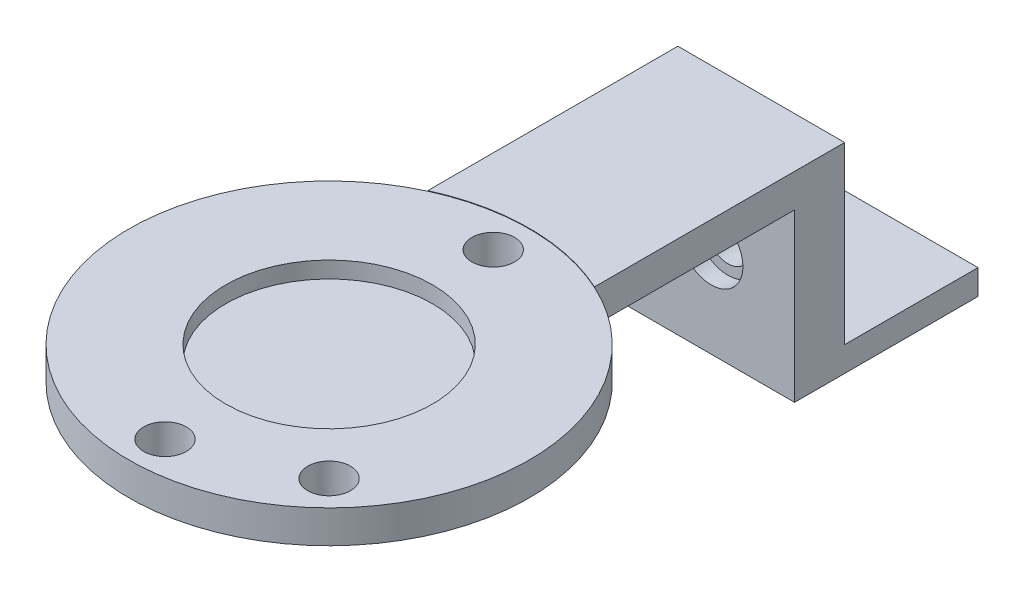
SolidWorks part; units mm, degrees
ref_plane "Front Plane" through (0, 0, 0) normal (0, 0, 1) x (1, 0, 0)
ref_plane "Top Plane" through (0, 0, 0) normal (0, 1, 0) x (1, 0, 0)
ref_plane "Right Plane" through (0, 0, 0) normal (1, 0, 0) x (0, 0, -1)
sketch "Sketch1" plane through (0, 0, 0) normal (0, 1, 0) x (1, 0, 0)
  circle A0 centre (0, 0) radius 30.5
extrude "Boss-Extrude1" add sketch "Sketch1" along normal blind 5
sketch "Sketch2" plane through (0, 5, 0) normal (0, 1, 0) x (1, 0, 0)
  circle A0 centre (0, 0) radius 15.75
extrude "Cut-Extrude1" cut sketch "Sketch2" against normal blind 2.5
sketch "Sketch3" plane through (0, 0, 0) normal (0, -1, 0) x (1, 0, 0)
  circle A0 centre (0, 0) radius 15.75
extrude "Boss-Extrude2" add sketch "Sketch3" along normal blind 2.5
sketch "Sketch4" plane through (0, 0, 0) normal (0, -1, 0) x (-1, 0, 0)
  circle A0 centre (0, 25) radius 3.25
  point P0 (0, 25)
  dimension "D1" = 25
extrude "Cut-Extrude2" cut sketch "Sketch4" against normal blind 5.08
sketch "Sketch5" plane through (0, 0, 0) normal (0, -1, 0) x (1, 0, 0)
  circle A0 centre (0, 25) radius 3.25
  point P0 (0, 25)
  dimension "D1" = 25
extrude "Cut-Extrude3" cut sketch "Sketch5" against normal blind 5.08
sketch "Sketch6" plane through (0, 0, 0) normal (0, -1, 0) x (1, 0, 0)
  circle A0 centre (0, 25) radius 3.25 construction
  circle A1 centre (17.6745, 17.6809) radius 3.25
  point P0 (17.6745, 17.6809)
  dimension "D1" = 25
  dimension "D2" = 19.13
extrude "Cut-Extrude4" cut sketch "Sketch6" against normal blind 5.08
sketch "Sketch7" plane through (0, 0, 0) normal (0, -1, 0) x (1, 0, 0)
  line L0 (0, 0) -> (0, -30.5)
  line L2 (-12.7, -27.7301) -> (12.7, -27.7301)
  line L3 (-12.7, -27.7301) -> (-12.7, -65.8301)
  line L4 (-12.7, -65.8301) -> (12.7, -65.8301)
  line L5 (12.7, -27.7301) -> (12.7, -65.8301)
  circle A0 centre (0, 0) radius 30.5 construction
  circle M8 centre (0, 0) radius 30.5
  dimension "D1" = 25.4
  dimension "D2" = 12.7
  dimension "D3" = 38.1
extrude "Boss-Extrude3" add sketch "Sketch7" against normal blind 5.08 contours L5 L3 L4 M8
sketch "Sketch8" plane through (0, 0, 0) normal (0, -1, 0) x (1, 0, 0)
  line L0 (-12.7, -27.7301) -> (-12.7, -65.8301) construction
  line L1 (12.7, -65.8301) -> (-12.7, -65.8301)
  line L2 (12.7, -65.8301) -> (12.7, -58.2101)
  line L3 (12.7, -58.2101) -> (-12.7, -58.2101)
  line L4 (-12.7, -65.8301) -> (-12.7, -58.2101)
  dimension "D1" = 7.62
extrude "Boss-Extrude4" add sketch "Sketch8" along normal blind 25.4
sketch "Sketch9" plane through (0, 0, -65.8301) normal (0, 0, -1) x (-1, 0, 0)
  line L0 (-12.7, 5.08) -> (-12.7, -25.4) construction
  line L1 (12.7, -25.4) -> (-12.7, -25.4)
  line L2 (12.7, -25.4) -> (12.7, -21.59)
  line L3 (12.7, -21.59) -> (-12.7, -21.59)
  line L4 (-12.7, -25.4) -> (-12.7, -21.59)
  dimension "D1" = 3.81
extrude "Boss-Extrude5" add sketch "Sketch9" along normal blind 20.32
sketch "Sketch10" plane through (0, 0, -65.8301) normal (0, 0, -1) x (-1, 0, 0)
  line L0 (0, -21.59) -> (0, 5.08)
  line L1 (12.7, -21.59) -> (-12.7, -21.59) construction
  line L2 (12.7, 5.08) -> (-12.7, 5.08) construction
  circle A0 centre (0, -11.43) radius 3.302
  dimension "D1" = 10.16
extrude "Cut-Extrude5" cut sketch "Sketch10" against normal blind 7.62 contours L0 A0
sketch "Sketch11" plane through (0, 0, -58.2101) normal (0, 0, 1) x (1, 0, 0)
  circle A0 centre (0, -11.43) radius 4.826
extrude "Cut-Extrude6" cut sketch "Sketch11" against normal blind 2.54
